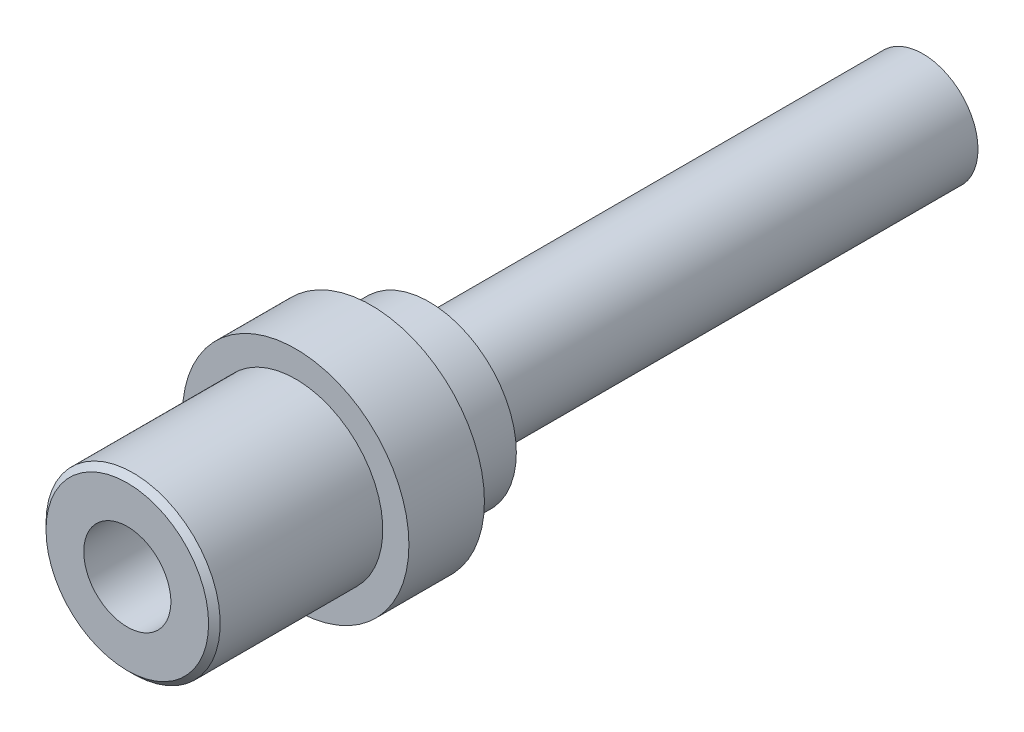
SolidWorks part; units mm, degrees
ref_plane "Спереди" through (0, 0, 0) normal (0, 0, 1) x (1, 0, 0)
ref_plane "Сверху" through (0, 0, 0) normal (0, 1, 0) x (1, 0, 0)
ref_plane "Справа" through (0, 0, 0) normal (1, 0, 0) x (0, 0, -1)
other "Configuration Table"
sketch "Эскиз1" plane through (0, 0, 0) normal (0, 0, 1) x (1, 0, 0)
  circle A0 centre (0, 0) radius 9.5
  dimension "D1" = 19
extrude "Бобышка-Вытянуть1" add sketch "Эскиз1" along normal blind 85
sketch "Эскиз2" plane through (0, 0, 85) normal (0, 0, 1) x (1, 0, 0)
  circle A0 centre (0, 0) radius 15
  dimension "D1" = 30
extrude "Бобышка-Вытянуть2" add sketch "Эскиз2" along normal blind 10
sketch "Эскиз3" plane through (0, 0, 95) normal (0, 0, 1) x (1, 0, 0)
  circle A0 centre (0, 0) radius 19.5
  dimension "D1" = 39
extrude "Бобышка-Вытянуть3" add sketch "Эскиз3" along normal blind 13
sketch "Эскиз4" plane through (0, 0, 108) normal (0, 0, 1) x (1, 0, 0)
  circle A0 centre (0, 0) radius 15
  dimension "D1" = 30
extrude "Бобышка-Вытянуть4" add sketch "Эскиз4" along normal blind 29
chamfer "Фаска1" distance 1 angle 45 1 edges at (15, 0, 137)
sketch "Эскиз5" plane through (0, 0, 0) normal (0, 0, -1) x (-1, 0, 0)
  circle A0 centre (0, 0) radius 7.5
  circle A1 centre (0, 0) radius 9.5 construction
  dimension "D1" = 2
extrude "Вырез-Вытянуть1" cut sketch "Эскиз5" against normal through all
